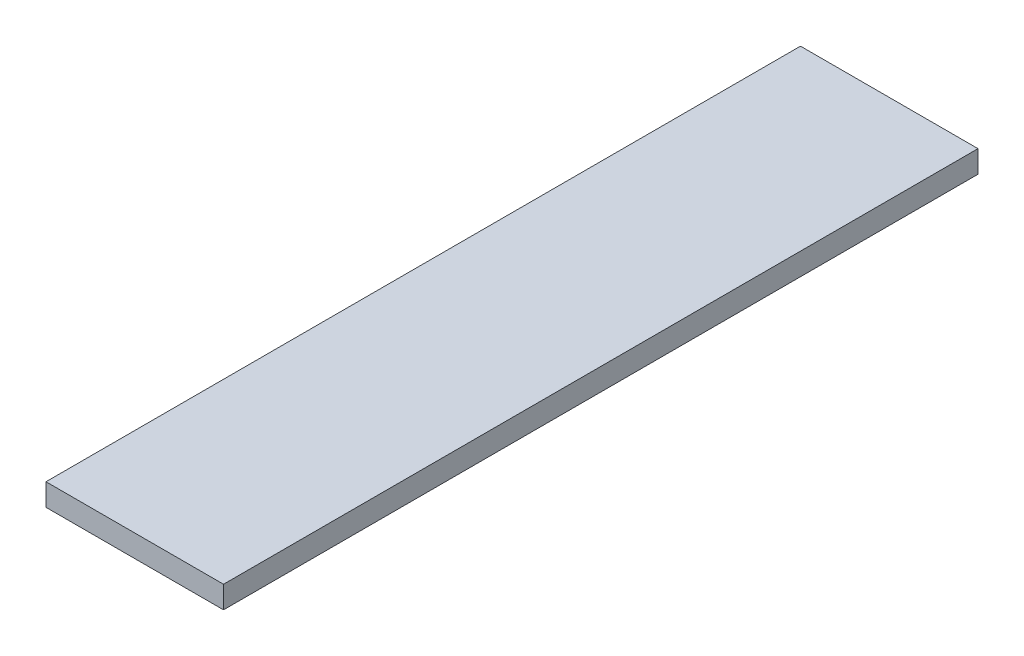
SolidWorks part; units mm, degrees
material "Maple"
ref_plane "Front Plane" through (0, 0, 0) normal (0, 0, 1) x (1, 0, 0)
ref_plane "Top Plane" through (0, 0, 0) normal (0, 1, 0) x (1, 0, 0)
ref_plane "Right Plane" through (0, 0, 0) normal (1, 0, 0) x (0, 0, -1)
sketch "Sketch1" plane through (0, 0, 0) normal (0, 1, 0) x (1, 0, 0)
  line L1 (0, 0) -> (101.6, 0)
  line L2 (0, 0) -> (0, 431.8)
  line L3 (0, 431.8) -> (101.6, 431.8)
  line L4 (101.6, 0) -> (101.6, 431.8)
  dimension "D1" = 431.8
  dimension "D2" = 101.6
extrude "Boss-Extrude1" add sketch "Sketch1" along normal blind 12.7
